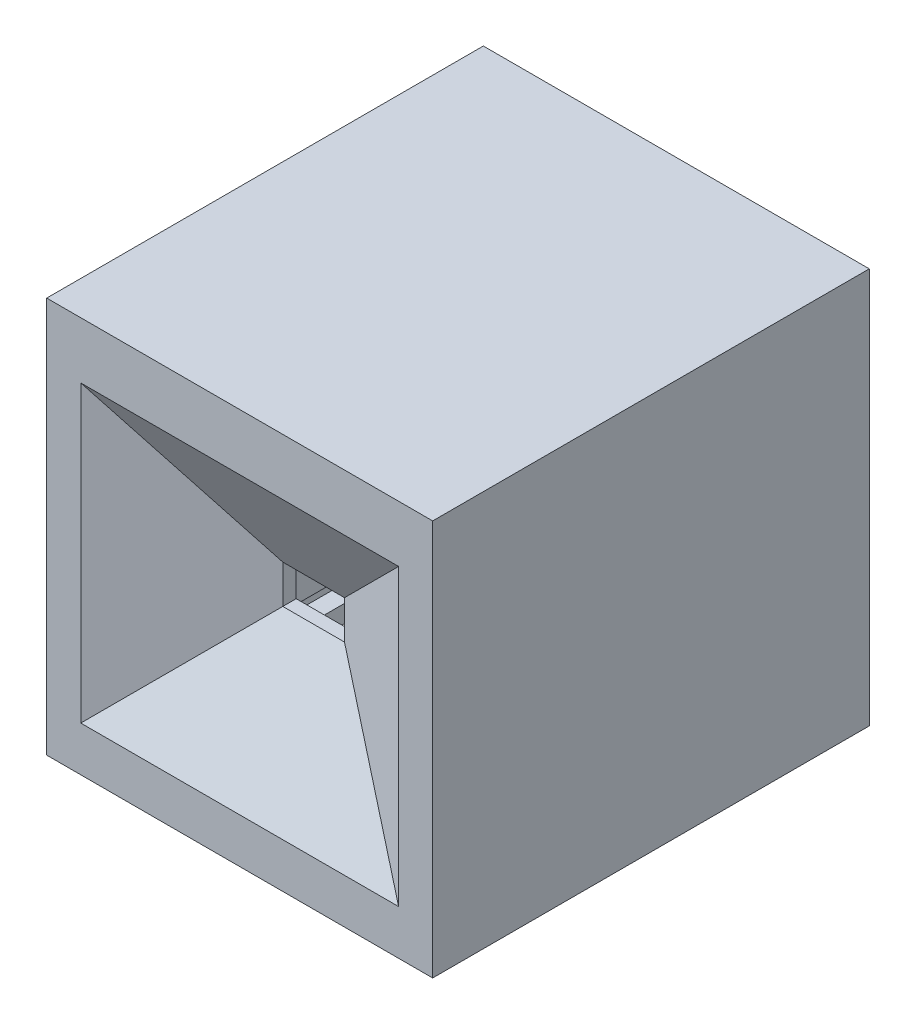
SolidWorks part; units mm, degrees
ref_plane "Front Plane" through (0, 0, 0) normal (0, 0, 1) x (1, 0, 0)
ref_plane "Top Plane" through (0, 0, 0) normal (0, 1, 0) x (1, 0, 0)
ref_plane "Right Plane" through (0, 0, 0) normal (1, 0, 0) x (0, 0, -1)
sketch "Sketch1" plane through (0, 0, 0) normal (0, 0, 1) x (1, 0, 0)
  line L10 (0, 0) -> (13.075, 0)
  line L15 (-13.575, -13.5) -> (-13.575, 13.5)
  line L16 (-13.575, 13.5) -> (13.575, 13.5)
  line L21 (13.575, -13.5) -> (13.575, 13.5)
  line L22 (-13.575, -13.5) -> (13.575, -13.5)
  line L28 (-12.425, -3.5) -> (-12.425, 3.5)
  line L29 (-12.425, 3.5) -> (-7.125, 3.5)
  line L30 (-7.125, -3.5) -> (-7.125, 3.5)
  line L31 (-12.425, -3.5) -> (-7.125, -3.5)
  line L32 (12.425, -3.5) -> (7.125, -3.5)
  line L33 (7.125, -3.5) -> (7.125, 3.5)
  line L34 (12.425, -3.5) -> (12.425, 3.5)
  line L35 (12.425, 3.5) -> (7.125, 3.5)
  line L36 (-2.65, -1.65) -> (-2.65, 1.65)
  line L37 (-2.65, 1.65) -> (2.65, 1.65)
  line L38 (2.65, -1.65) -> (2.65, 1.65)
  line L39 (-2.65, -1.65) -> (2.65, -1.65)
  circle A5 centre (10.325, 10.25) radius 1.175
  circle A6 centre (10.325, -10.25) radius 1.175
  circle A7 centre (-10.325, -10.25) radius 1.175
  circle A8 centre (-10.325, 10.25) radius 1.175
  point P0 (0, 0)
  point P16 (0, 0)
  point P31 (-9.775, 0)
  dimension "D10" = 2.35
  dimension "D11" = 2.35
  dimension "D12" = 2.35
  dimension "D13" = 2.35
  dimension "D18" = 13.075
ref_plane "Plane1" through (0, 0, 0) normal (0, 0, 1) x (1, 0, 0)
sketch "Sketch2" plane through (0, 0, 0) normal (0, 0, 1) x (1, 0, 0)
  line L0 (-16.575, 16.5) -> (-16.575, -16.5)
  line L5 (-16.575, -16.5) -> (16.575, -16.5)
  line L6 (16.575, 16.5) -> (16.575, -16.5)
  line L7 (-16.575, 16.5) -> (16.575, 16.5)
extrude "Boss-Extrude1" add sketch "Sketch2" along normal blind 7.5
ref_plane "Plane2" through (0, 0, 0) normal (0, 0, 1) x (1, 0, 0)
sketch "Sketch3" plane through (0, 0, 0) normal (0, 0, 1) x (1, 0, 0)
  circle A0 centre (10.325, 10.25) radius 1.175
  circle A1 centre (-10.325, 10.25) radius 1.175
  circle A2 centre (10.325, -10.25) radius 1.175
  circle A3 centre (-10.325, -10.25) radius 1.175
extrude "Cut-Extrude1" cut sketch "Sketch3" along normal blind 4.5
ref_plane "Plane3" through (0, 0, 0) normal (0, 0, 1) x (1, 0, 0)
sketch "Sketch4" plane through (0, 0, 0) normal (0, 0, 1) x (1, 0, 0)
  line L1 (12.425, -3.5) -> (7.125, -3.5)
  line L2 (12.425, -3.5) -> (12.425, 3.5)
  line L3 (12.425, 3.5) -> (7.125, 3.5)
  line L4 (7.125, -3.5) -> (7.125, 3.5)
  line L5 (-7.125, -3.5) -> (-12.425, -3.5)
  line L6 (-7.125, -3.5) -> (-7.125, 3.5)
  line L7 (-7.125, 3.5) -> (-12.425, 3.5)
  line L8 (-12.425, -3.5) -> (-12.425, 3.5)
extrude "Cut-Extrude2" cut sketch "Sketch4" along normal blind 3.5
ref_plane "Plane4" through (0, 0, 0) normal (0, 0, 1) x (1, 0, 0)
sketch "Sketch5" plane through (0, 0, 0) normal (0, 0, 1) x (1, 0, 0)
  line L1 (8.5467, -12.7134) -> (-8.766, -12.7134)
  line L2 (8.5467, -12.7134) -> (8.5467, -10.9049)
  line L3 (8.5467, -10.9049) -> (-8.766, -10.9049)
  line L4 (-8.766, -12.7134) -> (-8.766, -10.9049)
extrude "Cut-Extrude3" cut sketch "Sketch5" along normal blind 2
ref_plane "Plane5" through (0, 0, 0) normal (0, 0, 1) x (1, 0, 0)
sketch "Sketch6" plane through (0, 0, 0) normal (0, 0, 1) x (1, 0, 0)
  line L1 (2.65, -1.65) -> (-2.65, -1.65)
  line L2 (2.65, -1.65) -> (2.65, 1.65)
  line L3 (2.65, 1.65) -> (-2.65, 1.65)
  line L4 (-2.65, -1.65) -> (-2.65, 1.65)
extrude "Cut-Extrude4" cut sketch "Sketch6" along normal through all
chamfer "Chamfer3" distance 11 angle 30 4 edges at (-2.65, 0, 7.5) (0, -1.65, 7.5) (2.65, 0, 7.5) (0, 1.65, 7.5)
ref_plane "Plane7" through (0, 0, 0) normal (0, 0, 1) x (1, 0, 0)
sketch "Sketch7" plane through (0, 0, 0) normal (0, 0, 1) x (1, 0, 0)
  line L0 (16.575, 16.5) -> (-16.575, 16.5) construction
  line L1 (16.575, -16.5) -> (13.575, -16.5)
  line L2 (16.575, -16.5) -> (16.575, 16.5)
  line L3 (16.575, 16.5) -> (13.575, 16.5)
  line L4 (13.575, -16.5) -> (13.575, 16.5)
  line L6 (13.575, 13.5) -> (-16.575, 13.5)
  line L7 (13.575, 13.5) -> (13.575, 16.5)
  line L8 (13.575, 16.5) -> (-16.575, 16.5)
  line L9 (-16.575, 13.5) -> (-16.575, 16.5)
  line L10 (-13.575, 13.5) -> (-16.575, 13.5)
  line L11 (-13.575, 13.5) -> (-13.575, -16.5)
  line L12 (-13.575, -16.5) -> (-16.575, -16.5)
  line L13 (-16.575, 13.5) -> (-16.575, -16.5)
  dimension "D1" = 3
extrude "Boss-Extrude2" add sketch "Sketch7" against normal blind 30 contours L4 L1 L2 L3 | L9 L6 L4 L8 | L6 L13 L12 L11
sketch "Sketch8" plane through (0, 16.5, 0) normal (0, 1, 0) x (1, 0, 0)
  line L1 (-16.575, -7.5) -> (16.575, -7.5)
  line L2 (-16.575, -7.5) -> (-16.575, 30)
  line L3 (-16.575, 30) -> (16.575, 30)
  line L4 (16.575, -7.5) -> (16.575, 30)
extrude "Boss-Extrude3" add sketch "Sketch8" along normal blind 1
sketch "Sketch9" plane through (0, -16.5, 0) normal (0, -1, 0) x (1, 0, 0)
  line L0 (-13.575, -30) -> (-13.575, 0) construction
  line L1 (-13.575, -28) -> (-15.075, -28)
  line L2 (-13.575, -28) -> (-13.575, -26)
  line L3 (-13.575, -26) -> (-15.075, -26)
  line L4 (-15.075, -28) -> (-15.075, -26)
  line L5 (-13.575, -30) -> (-16.575, -30) construction
  line L6 (13.575, -30) -> (13.575, 0) construction
  line L7 (16.575, -30) -> (13.575, -30) construction
  line L8 (13.575, -28) -> (15.075, -28)
  line L9 (13.575, -28) -> (13.575, -26)
  line L10 (13.575, -26) -> (15.075, -26)
  line L11 (15.075, -28) -> (15.075, -26)
  dimension "D1" = 2
  dimension "D2" = 2
  dimension "D3" = 1.5
  dimension "D4" = 2
  dimension "D5" = 2
  dimension "D6" = 1.5
extrude "Cut-Extrude5" cut sketch "Sketch9" against normal blind 31.5
sketch "Sketch10" plane through (0, 13.5, 0) normal (0, -1, 0) x (1, 0, 0)
  line L1 (-13.575, -28) -> (13.575, -28)
  line L2 (-13.575, -28) -> (-13.575, -26)
  line L3 (-13.575, -26) -> (13.575, -26)
  line L4 (13.575, -28) -> (13.575, -26)
extrude "Cut-Extrude6" cut sketch "Sketch10" against normal blind 1.5
sketch "Sketch11" plane through (0, 0, -30) normal (0, 0, -1) x (-1, 0, 0)
  line L0 (-13.575, -16.5) -> (-13.575, 13.5) construction
  line L1 (-13.575, -15) -> (-15.075, -15)
  line L2 (-13.575, -15) -> (-13.575, -13)
  line L3 (-13.575, -13) -> (-15.075, -13)
  line L4 (-15.075, -15) -> (-15.075, -13)
  line L5 (-16.575, -16.5) -> (-13.575, -16.5) construction
  line L6 (13.575, 13.5) -> (13.575, -16.5) construction
  line L7 (13.575, -15) -> (15.075, -15)
  line L8 (13.575, -15) -> (13.575, -13)
  line L9 (13.575, -13) -> (15.075, -13)
  line L10 (15.075, -15) -> (15.075, -13)
  line L11 (13.575, -16.5) -> (16.575, -16.5) construction
  dimension "D1" = 1.5
  dimension "D2" = 2
  dimension "D3" = 1.5
  dimension "D4" = 2
  dimension "D5" = 1.5
  dimension "D6" = 1.5
extrude "Cut-Extrude7" cut sketch "Sketch11" against normal up to surface (30 mm away)
ref_plane "Plane12" through (13.575, -13, -30) normal (1, 0, 0) x (0, 0, -1)
sketch "Sketch14" plane through (0, 0, 0) normal (0, 0, -1) x (-1, 0, 0)
  line L1 (-15.075, -13) -> (15.075, -13)
  line L2 (-15.075, -13) -> (-15.075, -15)
  line L3 (-15.075, -15) -> (15.075, -15)
  line L4 (15.075, -13) -> (15.075, -15)
extrude "Cut-Extrude8" cut sketch "Sketch14" against normal blind 1.5
